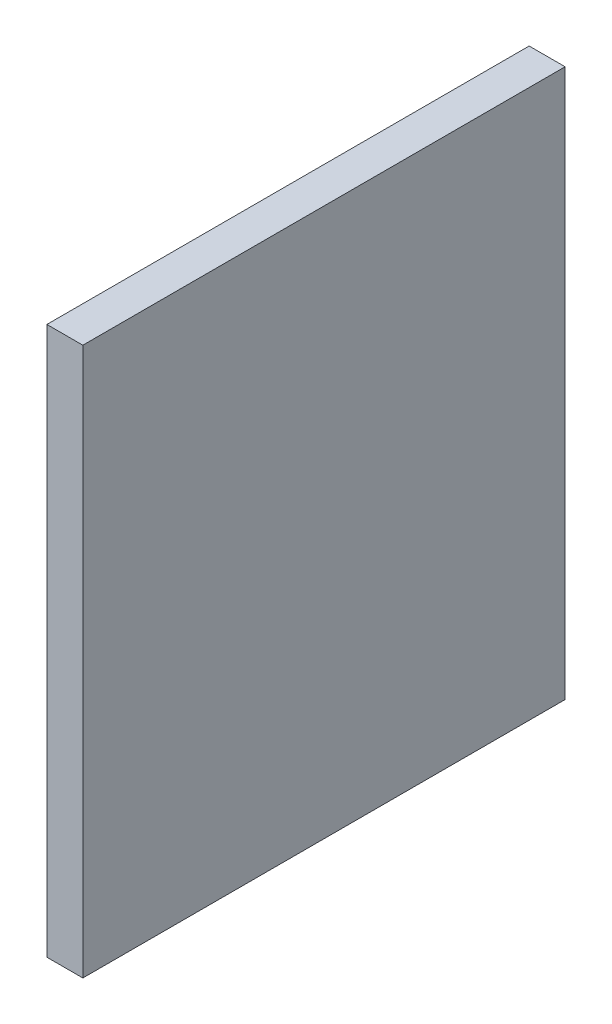
SolidWorks part; units mm, degrees
ref_plane "Front Plane" through (0, 0, 0) normal (0, 0, 1) x (1, 0, 0)
ref_plane "Top Plane" through (0, 0, 0) normal (0, 1, 0) x (1, 0, 0)
ref_plane "Right Plane" through (0, 0, 0) normal (1, 0, 0) x (0, 0, -1)
sketch "Sketch1" plane through (0, 0, 0) normal (1, 0, 0) x (0, 0, -1)
  line L1 (-10.9753, 38.1941) -> (56.0807, 38.1941)
  line L2 (-10.9753, 38.1941) -> (-10.9753, -38.0059)
  line L3 (-10.9753, -38.0059) -> (56.0807, -38.0059)
  line L4 (56.0807, 38.1941) -> (56.0807, -38.0059)
  dimension "D1" = 67.056
  dimension "D2" = 76.2
extrude "Boss-Extrude1" add sketch "Sketch1" along normal blind 5
